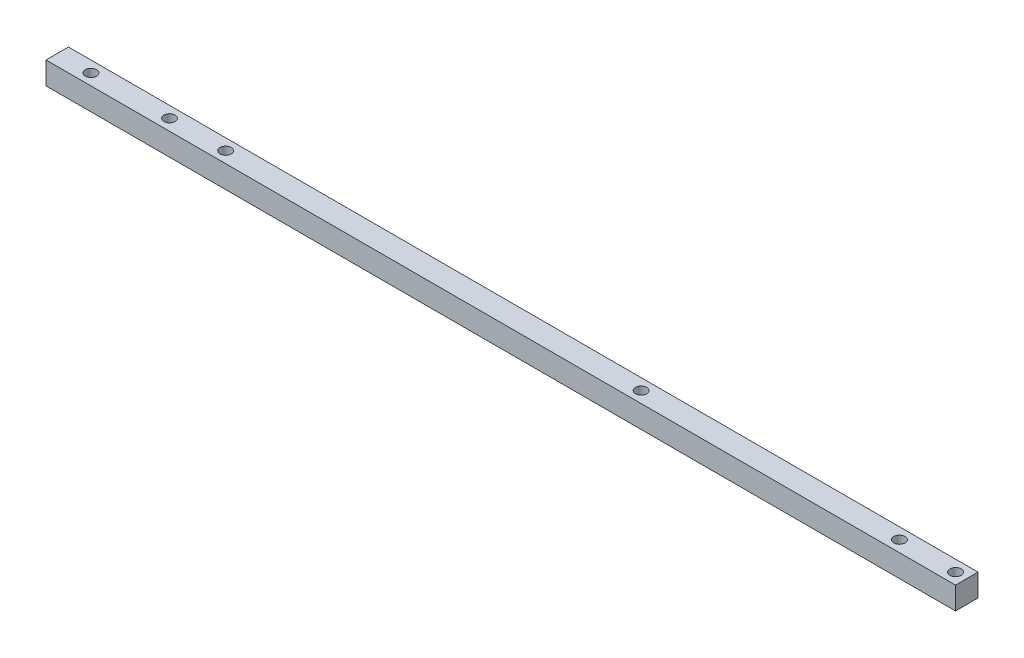
SolidWorks part; units mm, degrees
ref_plane "Front Plane" through (0, 0, 0) normal (0, 0, 1) x (1, 0, 0)
ref_plane "Top Plane" through (0, 0, 0) normal (0, 1, 0) x (1, 0, 0)
ref_plane "Right Plane" through (0, 0, 0) normal (1, 0, 0) x (0, 0, -1)
sketch "Sketch1" plane through (0, 0, 0) normal (0, 1, 0) x (1, 0, 0)
  line L1 (0, 0) -> (257.175, 0)
  line L2 (0, 0) -> (0, 6.35)
  line L3 (0, 6.35) -> (257.175, 6.35)
  line L4 (257.175, 0) -> (257.175, 6.35)
  circle A0 centre (31.75, 3.175) radius 1.5875
  circle A1 centre (165.1, 3.175) radius 1.5875
  circle A2 centre (238.125, 3.175) radius 1.5875
  circle A3 centre (9.525, 3.175) radius 1.5875
  circle A4 centre (47.625, 3.175) radius 1.5875
  circle A5 centre (254, 3.175) radius 1.5875
  point P14 (257.175, 3.175)
  dimension "D3" = 3.175
  dimension "D1" = 257.175
  dimension "D2" = 6.35
  dimension "D4" = 31.75
  dimension "D5" = 165.1
  dimension "D6" = 238.125
  dimension "D7" = 9.525
  dimension "D8" = 47.625
  dimension "D9" = 206.375
extrude "Boss-Extrude1" add sketch "Sketch1" along normal blind 6.35
